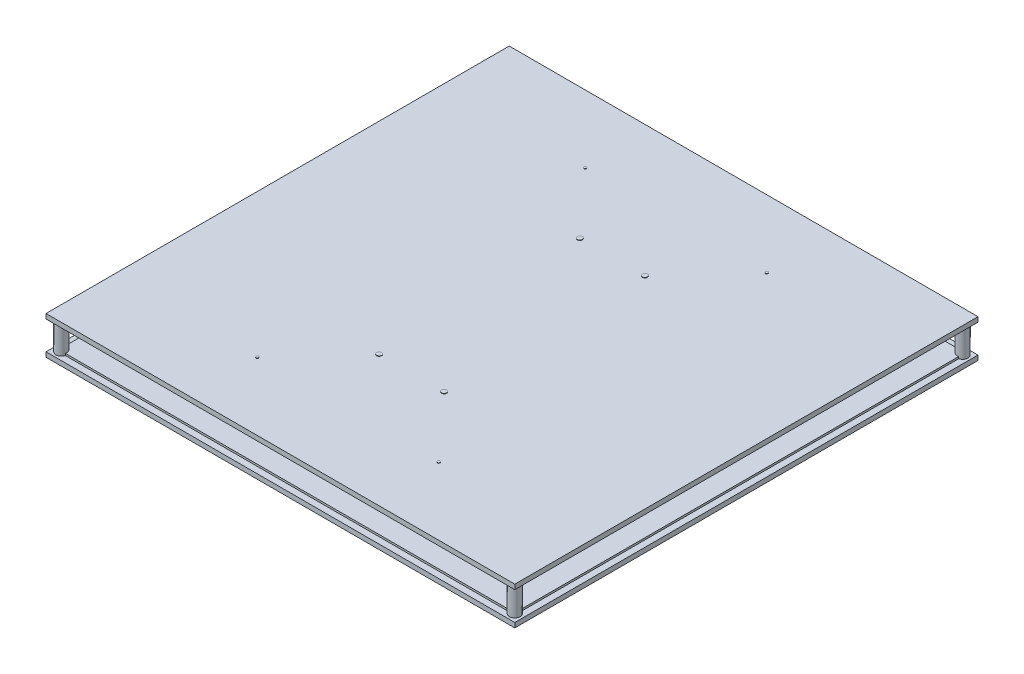
SolidWorks part; units mm, degrees
ref_plane "Front Plane" through (0, 0, 0) normal (0, 0, 1) x (1, 0, 0)
ref_plane "Top Plane" through (0, 0, 0) normal (0, 1, 0) x (1, 0, 0)
ref_plane "Right Plane" through (0, 0, 0) normal (1, 0, 0) x (0, 0, -1)
sketch "Sketch1" plane through (0, 0, 0) normal (0, 1, 0) x (1, 0, 0)
  line L1 (-155.3961, -153.5521) -> (155.3961, -153.5521)
  line L2 (-155.3961, -153.5521) -> (-155.3961, 153.5521)
  line L3 (-155.3961, 153.5521) -> (155.3961, 153.5521)
  line L4 (155.3961, -153.5521) -> (155.3961, 153.5521)
  line L5 (-155.3961, -153.5521) -> (155.3961, 153.5521) construction
  line L6 (-155.3961, 153.5521) -> (155.3961, -153.5521) construction
  point P0 (0, 0)
extrude "Boss-Extrude1" add sketch "Sketch1" along normal blind 3.175 contours L2 L1 L4 L3
sketch "Sketch2" plane through (0, 3.175, 0) normal (0, 1, 0) x (1, 0, 0)
  line L13 (151.1543, 149.3103) -> (-151.1543, 149.3103)
  line L14 (151.1543, 149.3103) -> (151.1543, -149.3103)
  line L15 (151.1543, -149.3103) -> (-151.1543, -149.3103)
  line L16 (-151.1543, 149.3103) -> (-151.1543, -149.3103)
extrude "Boss-Extrude2" add sketch "Sketch2" along normal blind 1.27 contours L14 L13 L16 L15
sketch "Sketch4" plane through (0, 0, -153.5521) normal (0, 0, -1) x (-1, 0, 0)
  line L0 (155.3961, 3.175) -> (155.3961, 25.1714)
  line L1 (-155.3961, 3.175) -> (-155.3961, 25.1714)
sketch "Sketch5" plane through (0, 0, 153.5521) normal (0, 0, 1) x (1, 0, 0)
  line L0 (155.3961, 3.175) -> (155.3961, 25.1714)
  line L1 (-155.3961, 3.175) -> (-155.3961, 25.1714)
sketch3d "3DSketch1"
  line L0 (-155.3961, 25.1714, -153.5521) -> (-155.3961, 25.1714, 153.5521)
  line L1 (-155.3961, 25.1714, 153.5521) -> (155.3961, 25.1714, 153.5521)
  line L2 (155.3961, 25.1714, 153.5521) -> (155.3961, 25.1714, -153.5521)
  line L3 (155.3961, 25.1714, -153.5521) -> (-155.3961, 25.1714, -153.5521)
extrude "Boss-Extrude4" add sketch "3DSketch1" along direction (0, -1, 0) on the side of the normal blind 3.175 separate body contours L0 L1 L2 L3
sketch "Sketch6" plane through (0, 25.1714, 0) normal (0, 1, 0) x (1, 0, 0)
  line L1 (155.3961, 153.5521) -> (-155.3961, 153.5521) construction
  line L5 (0, -153.5521) -> (0, 153.5521)
  line L6 (-155.3961, -153.5521) -> (155.3961, -153.5521) construction
  line L7 (-155.3961, 0) -> (155.3961, 0)
  line L8 (-155.3961, 153.5521) -> (-155.3961, -153.5521) construction
  line L9 (155.3961, -153.5521) -> (155.3961, 153.5521) construction
  circle A0 centre (60.1461, 108.7163) radius 0.911
  circle A1 centre (21.5381, 66.5523) radius 1.6837
  circle A2 centre (-21.5381, 66.5523) radius 1.6837
  circle A3 centre (-60.1461, 108.7163) radius 0.911
  circle A4 centre (21.5381, -66.5523) radius 1.6837
  circle A5 centre (60.1461, -108.7163) radius 0.911
  circle A6 centre (-21.5381, -66.5523) radius 1.6837
  circle A7 centre (-60.1461, -108.7163) radius 0.911
extrude "Boss-Extrude7" add sketch "Sketch6" along normal blind 0.254 contours A7 | A6 | A3 | A2 | A1 | A0 | A4 | A5
sketch "Sketch7" plane through (0, 0, 0) normal (0, -1, 0) x (1, 0, 0)
  line L0 (-155.3961, 153.5521) -> (-150.3161, 153.5521)
  line L1 (-155.3961, 153.5521) -> (155.3961, 153.5521) construction
  circle A0 centre (-150.3161, 148.4721) radius 3.556
  circle A1 centre (150.3161, 148.4721) radius 3.556
  circle A2 centre (150.3161, -148.4721) radius 3.556
  circle A3 centre (-150.3161, -148.4721) radius 3.556
extrude "Boss-Extrude8" add sketch "Sketch7" against normal blind 23.876 contours A3 | A2 | A1 | A0
